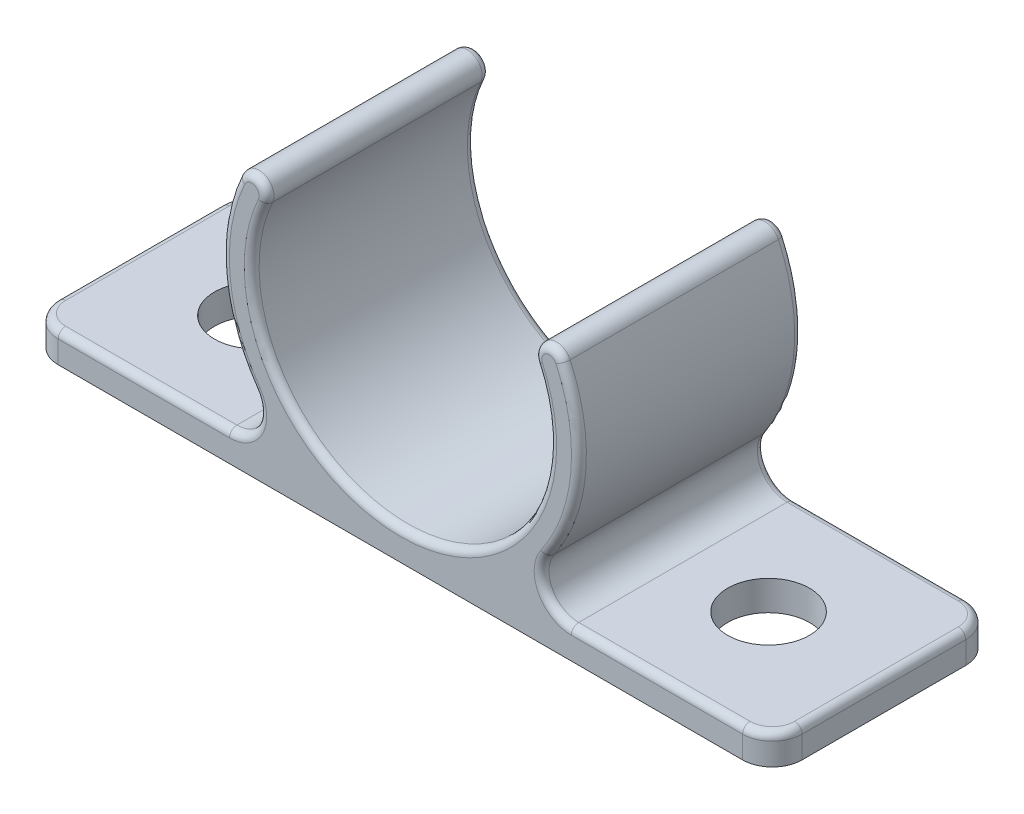
SolidWorks part; units mm, degrees
ref_plane "Front Plane" through (0, 0, 0) normal (0, 0, 1) x (1, 0, 0)
ref_plane "Top Plane" through (0, 0, 0) normal (0, 1, 0) x (1, 0, 0)
ref_plane "Right Plane" through (0, 0, 0) normal (1, 0, 0) x (0, 0, -1)
sketch "Sketch1" plane through (0, 0, 0) normal (0, 0, 1) x (1, 0, 0)
  line L0 (6.6332, -10) -> (25, -10)
  line L1 (-25, -12) -> (25, -12)
  line L2 (-25, -12) -> (-25, -10)
  line L3 (-25, -10) -> (-6.6332, -10)
  line L4 (25, -12) -> (25, -10)
  circle A0 centre (0, 0) radius 10 construction
  arc A1 (9.0909, 4.166) -> (-9.0909, 4.166) centre (0, 0) cw
  arc A2 (10.9091, 4.9992) -> (6.6332, -10) centre (0, 0) cw
  arc A5 (-10.9091, 4.9992) -> (-9.0909, 4.166) centre (-10, 4.5826) cw
  arc A6 (9.0909, 4.166) -> (10.9091, 4.9992) centre (10, 4.5826) cw
  arc A7 (-6.6332, -10) -> (-10.9091, 4.9992) centre (0, 0) cw
  arc A8 (10.9091, 4.9992) -> (-10.9091, 4.9992) centre (0, 0) cw construction
  point P15 (0, -12)
  dimension "D1" = 20
  dimension "D2" = 2
  dimension "D3" = 20
  dimension "D4" = 2
  dimension "D5" = 50
extrude "Boss-Extrude1" add sketch "Sketch1" along normal blind 15
fillet "Fillet1" radius 2 6 edges at (25, -11, 0) (25, -11, 15) (-25, -11, 0) (-25, -11, 15) (-6.6332, -10, 7.5) (6.6332, -10, 7.5)
fillet "Fillet2" radius 0.5 24 edges at (-9.7163, -8.9258, 0) (-11.9522, -1.0699, 0) (-9.5834, 5.4917, 0) (0, -10, 0) (9.5834, 5.4917, 0) (11.9522, -1.0699, 0) (9.7163, -8.9258, 0) (17.2446, -10, 0) (24.4142, -10, 0.5858) (25, -10, 7.5) (24.4142, -10, 14.4142) (17.2446, -10, 15) (9.7163, -8.9258, 15) (11.9522, -1.0699, 15) (9.5834, 5.4917, 15) (0, -10, 15) (-9.5834, 5.4917, 15) (-11.9522, -1.0699, 15) (-9.7163, -8.9258, 15) (-17.2446, -10, 15) (-24.4142, -10, 14.4142) (-25, -10, 7.5) (-24.4142, -10, 0.5858) (-17.2446, -10, 0)
hole_wizard "M5 Clearance Hole1" positions "Sketch2" profile "Sketch3" hole size "M5" standard "ISO" end condition up to next
sketch "Sketch2" plane through (0, -10, 0) normal (0, 1, 0) x (1, 0, 0)
  line L0 (-24.5, -2) -> (-24.5, -13) construction
  line L1 (-11.4891, -0.5) -> (-23, -0.5) construction
  line L2 (23, -0.5) -> (11.4891, -0.5) construction
  line L3 (24.5, -13) -> (24.5, -2) construction
  point P0 (-17.2446, -7.5)
  point P2 (17.2446, -7.5)
  point P7 (-24.5, -7.5)
  point P10 (-17.2446, -0.5)
  point P14 (17.2446, -0.5)
  point P17 (24.5, -7.5)
sketch "Sketch3" plane through (-17.2446, -10, 7.5) normal (1, 0, 0) x (0, 0, 1)
  line L0 (0, 0) -> (0, 2)
  line L1 (0, 2) -> (2.75, 2)
  line L2 (2.75, 2) -> (2.75, 0)
  line L5 (2.75, 0) -> (0, 0)
  line L11 (0, -6.35) -> (0, 107.95) construction
  dimension "Thru Hole Dia." = 5.5
  dimension "Thru Hole Depth" = 2
